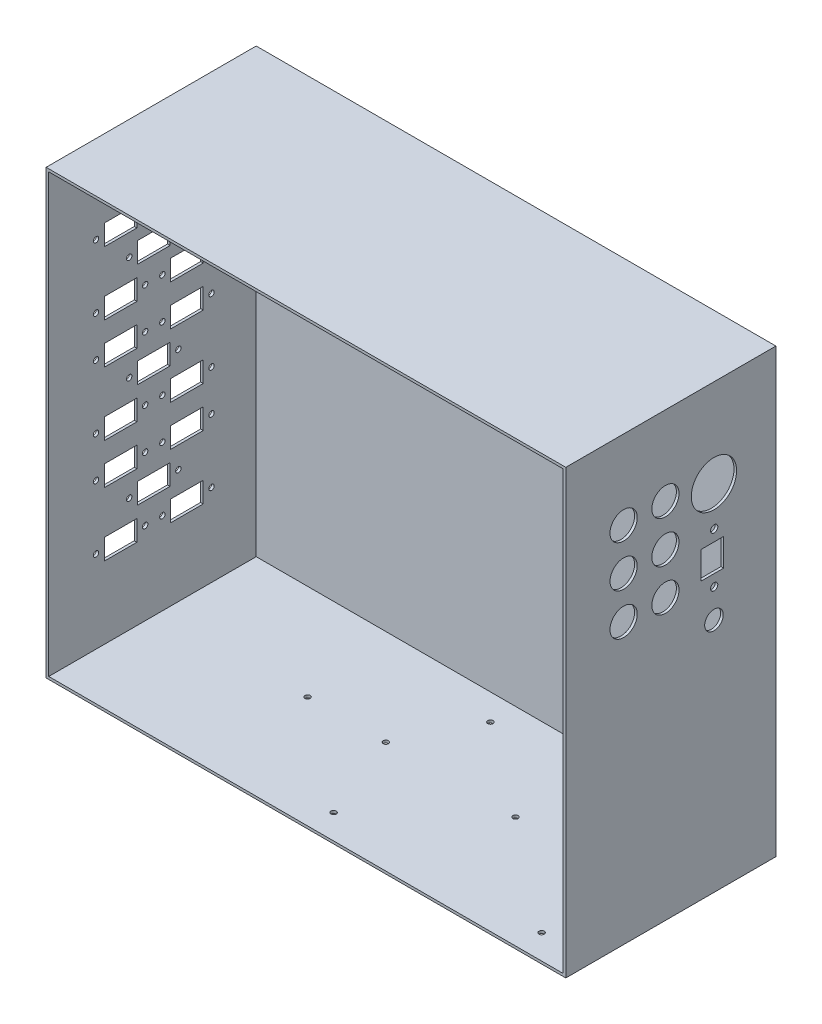
SolidWorks part; units mm, degrees
ref_plane "Front Plane" through (0, 0, 0) normal (0, 0, 1) x (1, 0, 0)
ref_plane "Top Plane" through (0, 0, 0) normal (0, 1, 0) x (1, 0, 0)
ref_plane "Right Plane" through (0, 0, 0) normal (1, 0, 0) x (0, 0, -1)
sketch "Sketch2" plane through (0, 0, 0) normal (0, 0, 1) x (1, 0, 0)
  line L1 (-149.225, 127) -> (149.225, 127)
  line L2 (-149.225, 127) -> (-149.225, -127)
  line L3 (-149.225, -127) -> (149.225, -127)
  line L4 (149.225, 127) -> (149.225, -127)
  line L5 (-149.225, 127) -> (149.225, -127) construction
  line L6 (-149.225, -127) -> (149.225, 127) construction
  point P0 (0, 0)
  dimension "D1" = 298.45
  dimension "D2" = 254
extrude "Boss-Extrude1" add sketch "Sketch2" along normal blind 120.65
shell "Shell1" thickness 1.5
sketch "Sketch3" plane through (149.225, 0, 0) normal (1, 0, 0) x (0, 0, -1)
  line L0 (-40.4352, 50.2841) -> (-40.4352, 57.3961) construction
  line L1 (-24.3484, 28.5671) -> (-24.2403, 50.2841) construction
  line L2 (-101.6, 95.7164) -> (-19.05, 95.7164) construction
  line L3 (-101.6, 95.7164) -> (-101.6, -88.9) construction
  line L4 (-101.6, -88.9) -> (-19.05, -88.9) construction
  line L5 (-19.05, 95.7164) -> (-19.05, -88.9) construction
  line L6 (-24.3484, 28.5671) -> (-30.4022, 28.5671) construction
  line L7 (-46.489, 28.5671) -> (-46.5749, 50.2841) construction
  line L8 (-24.2403, 50.2841) -> (-30.4022, 50.2841) construction
  line L9 (-30.4022, 50.2841) -> (-30.4022, 57.4161) construction
  line L10 (-40.4352, 28.5671) -> (-46.489, 28.5671) construction
  line L11 (-40.4352, 21.4551) -> (-40.4352, 28.5671) construction
  line L12 (-40.4352, 21.4551) -> (-30.4022, 21.4551) construction
  line L13 (-30.4022, 21.4551) -> (-30.4022, 28.5671) construction
  line L14 (-40.4352, 57.3961) -> (-30.4022, 57.4161) construction
  line L15 (-40.4352, 50.2841) -> (-46.5749, 50.2841) construction
  line L16 (-46.532, 39.4256) -> (-24.2943, 39.4256) construction
  line L17 (-35.4187, 23.6) -> (-35.4187, 57.4061) construction
  line L18 (-43.0873, 31.5516) -> (-43.0873, 47.2996)
  line L19 (-43.0873, 31.5516) -> (-30.0063, 31.5516)
  line L20 (-30.0063, 31.5516) -> (-30.0063, 47.2996)
  line L21 (-43.0873, 47.2996) -> (-30.0063, 47.2996)
  line L24 (-120.65, -127) -> (-120.65, 127) construction
  line L25 (-120.65, -127) -> (0, -127) construction
  circle A0 centre (-87.4395, 33.5559) radius 7.8105
  circle A1 centre (-63.4395, 33.5559) radius 7.8105
  circle A2 centre (-63.4395, 57.5559) radius 7.8105
  circle A3 centre (-63.4395, 81.5559) radius 7.8105
  circle A4 centre (-87.4395, 57.5559) radius 7.8105
  circle A5 centre (-87.4395, 81.5559) radius 7.8105
  circle A6 centre (-35.4187, 25.0111) radius 2.0638
  circle A7 centre (-35.4187, 53.8401) radius 2.0638
  circle A8 centre (-35.56, 8.5011) radius 5.334
  circle A9 centre (-35.56, 76.3489) radius 13.0175
  dimension "D1" = 15.621
  dimension "D4" = 82.55
  dimension "D5" = 14.1605
  dimension "D7" = 19.3675
  dimension "D10" = 28.829
  dimension "D11" = 6.5405
  dimension "D21" = 16.51
  dimension "D6" = 14.1605
  dimension "D8" = 0.512
  dimension "D9" = 13.081
  dimension "D12" = 21.717
  dimension "D13" = 15.748
  dimension "D14" = 7.6686
  dimension "D15" = 0.285
  dimension "D16" = 10.033
  dimension "D17" = 0.227
  dimension "D18" = 16.51
  dimension "D19" = 19.05
  dimension "D20" = 38.1
  dimension "D22" = 0.115
  dimension "D23" = 6.1397
  dimension "D24" = 16.51
  dimension "D2" = 2
  dimension "D3" = 3
extrude "PT Connector Cutouts" cut sketch "Sketch3" against normal up to next
sketch "Sketch4" plane through (-149.225, 0, 0) normal (-1, 0, 0) x (0, 0, 1)
  line L0 (41.275, 72.2563) -> (41.275, 84.0563) construction
  line L1 (31.925, 84.0563) -> (31.925, 72.2563)
  line L2 (31.925, 84.0563) -> (50.625, 84.0563)
  line L3 (50.625, 84.0563) -> (50.625, 72.2563)
  line L4 (31.925, 72.2563) -> (50.625, 72.2563)
  line L10 (22.225, -88.9) -> (98.425, -88.9) construction
  line L11 (22.225, -88.9) -> (22.225, 88.9) construction
  line L12 (22.225, 88.9) -> (98.425, 88.9) construction
  line L13 (98.425, -88.9) -> (98.425, 88.9) construction
  line L73 (120.65, 127) -> (0, 127) construction
  line L74 (0, 127) -> (0, -127) construction
  line L75 (31.925, 86.0563) -> (27.1625, 84.0563) construction
  line L81 (31.925, 70.2563) -> (50.625, 70.2563) construction
  line L83 (31.925, 86.0563) -> (50.625, 86.0563) construction
  line L84 (50.625, 86.0563) -> (55.3875, 84.0563) construction
  line L85 (31.925, 70.2563) -> (27.1625, 72.2563) construction
  line L86 (50.625, 70.2563) -> (55.3875, 72.2563) construction
  line L87 (31.925, 84.0563) -> (50.625, 84.0563) construction
  line L89 (31.925, 72.2563) -> (50.625, 72.2563) construction
  line L91 (31.925, 84.0563) -> (50.625, 84.0563) construction
  line L92 (24.275, 72.2563) -> (24.275, 84.0563) construction
  line L93 (24.275, 72.2563) -> (27.1625, 72.2563) construction
  line L94 (58.275, 72.2563) -> (58.275, 84.0563) construction
  line L95 (24.275, 84.0563) -> (27.1625, 84.0563) construction
  line L98 (55.3875, 84.0563) -> (58.275, 84.0563) construction
  line L99 (55.3875, 72.2563) -> (58.275, 72.2563) construction
  line L100 (31.925, 72.2563) -> (50.625, 72.2563) construction
  line L170 (120.65, -127) -> (0, -127) construction
  line L171 (70.025, 84.0563) -> (70.025, 72.2563)
  line L172 (70.025, 84.0563) -> (88.725, 84.0563)
  line L173 (88.725, 84.0563) -> (88.725, 72.2563)
  line L174 (70.025, 72.2563) -> (88.725, 72.2563)
  line L175 (79.375, 72.2563) -> (79.375, 84.0563) construction
  line L176 (70.025, 86.0563) -> (65.2625, 84.0563) construction
  line L177 (70.025, 70.2563) -> (88.725, 70.2563) construction
  line L178 (70.025, 86.0563) -> (88.725, 86.0563) construction
  line L179 (88.725, 86.0563) -> (93.4875, 84.0563) construction
  line L180 (70.025, 70.2563) -> (65.2625, 72.2563) construction
  line L181 (88.725, 70.2563) -> (93.4875, 72.2563) construction
  line L182 (70.025, 84.0563) -> (88.725, 84.0563) construction
  line L183 (70.025, 72.2563) -> (88.725, 72.2563) construction
  line L184 (70.025, 84.0563) -> (88.725, 84.0563) construction
  line L185 (62.375, 72.2563) -> (62.375, 84.0563) construction
  line L186 (62.375, 72.2563) -> (65.2625, 72.2563) construction
  line L187 (96.375, 72.2563) -> (96.375, 84.0563) construction
  line L188 (62.375, 84.0563) -> (65.2625, 84.0563) construction
  line L189 (93.4875, 84.0563) -> (96.375, 84.0563) construction
  line L190 (93.4875, 72.2563) -> (96.375, 72.2563) construction
  line L191 (70.025, 72.2563) -> (88.725, 72.2563) construction
  line L213 (70.025, 47.5438) -> (70.025, 35.7438)
  line L214 (70.025, 47.5438) -> (88.725, 47.5438)
  line L215 (88.725, 47.5438) -> (88.725, 35.7438)
  line L216 (70.025, 35.7438) -> (88.725, 35.7438)
  line L217 (79.375, 35.7438) -> (79.375, 47.5438) construction
  line L218 (70.025, 49.5438) -> (65.2625, 47.5438) construction
  line L219 (70.025, 33.7438) -> (88.725, 33.7438) construction
  line L220 (70.025, 49.5438) -> (88.725, 49.5438) construction
  line L221 (88.725, 49.5438) -> (93.4875, 47.5438) construction
  line L222 (70.025, 33.7438) -> (65.2625, 35.7438) construction
  line L223 (88.725, 33.7438) -> (93.4875, 35.7438) construction
  line L224 (70.025, 47.5438) -> (88.725, 47.5438) construction
  line L225 (70.025, 35.7438) -> (88.725, 35.7438) construction
  line L226 (70.025, 47.5438) -> (88.725, 47.5438) construction
  line L227 (62.375, 35.7438) -> (62.375, 47.5438) construction
  line L228 (62.375, 35.7438) -> (65.2625, 35.7438) construction
  line L229 (96.375, 35.7438) -> (96.375, 47.5438) construction
  line L230 (62.375, 47.5438) -> (65.2625, 47.5438) construction
  line L231 (93.4875, 47.5438) -> (96.375, 47.5438) construction
  line L232 (93.4875, 35.7438) -> (96.375, 35.7438) construction
  line L233 (70.025, 35.7438) -> (88.725, 35.7438) construction
  line L234 (70.025, 24.1563) -> (70.025, 12.3563)
  line L235 (70.025, 24.1563) -> (88.725, 24.1563)
  line L236 (88.725, 24.1563) -> (88.725, 12.3563)
  line L237 (70.025, 12.3563) -> (88.725, 12.3563)
  line L238 (79.375, 12.3563) -> (79.375, 24.1563) construction
  line L239 (70.025, 26.1563) -> (65.2625, 24.1563) construction
  line L240 (70.025, 10.3563) -> (88.725, 10.3563) construction
  line L241 (70.025, 26.1563) -> (88.725, 26.1563) construction
  line L242 (88.725, 26.1563) -> (93.4875, 24.1563) construction
  line L243 (70.025, 10.3563) -> (65.2625, 12.3563) construction
  line L244 (88.725, 10.3563) -> (93.4875, 12.3563) construction
  line L245 (70.025, 24.1563) -> (88.725, 24.1563) construction
  line L246 (70.025, 12.3563) -> (88.725, 12.3563) construction
  line L247 (70.025, 24.1563) -> (88.725, 24.1563) construction
  line L248 (62.375, 12.3563) -> (62.375, 24.1563) construction
  line L249 (62.375, 12.3563) -> (65.2625, 12.3563) construction
  line L250 (96.375, 12.3563) -> (96.375, 24.1563) construction
  line L251 (62.375, 24.1563) -> (65.2625, 24.1563) construction
  line L252 (93.4875, 24.1563) -> (96.375, 24.1563) construction
  line L253 (93.4875, 12.3563) -> (96.375, 12.3563) construction
  line L254 (70.025, 12.3563) -> (88.725, 12.3563) construction
  line L276 (70.025, -12.3562) -> (70.025, -24.1562)
  line L277 (70.025, -12.3562) -> (88.725, -12.3562)
  line L278 (88.725, -12.3562) -> (88.725, -24.1562)
  line L279 (70.025, -24.1562) -> (88.725, -24.1562)
  line L280 (79.375, -24.1562) -> (79.375, -12.3562) construction
  line L281 (70.025, -10.3562) -> (65.2625, -12.3562) construction
  line L282 (70.025, -26.1562) -> (88.725, -26.1562) construction
  line L283 (70.025, -10.3562) -> (88.725, -10.3562) construction
  line L284 (88.725, -10.3562) -> (93.4875, -12.3562) construction
  line L285 (70.025, -26.1562) -> (65.2625, -24.1562) construction
  line L286 (88.725, -26.1562) -> (93.4875, -24.1562) construction
  line L287 (70.025, -12.3562) -> (88.725, -12.3562) construction
  line L288 (70.025, -24.1562) -> (88.725, -24.1562) construction
  line L289 (70.025, -12.3562) -> (88.725, -12.3562) construction
  line L290 (62.375, -24.1562) -> (62.375, -12.3562) construction
  line L291 (62.375, -24.1562) -> (65.2625, -24.1562) construction
  line L292 (96.375, -24.1562) -> (96.375, -12.3562) construction
  line L293 (62.375, -12.3562) -> (65.2625, -12.3562) construction
  line L294 (93.4875, -12.3562) -> (96.375, -12.3562) construction
  line L295 (93.4875, -24.1562) -> (96.375, -24.1562) construction
  line L296 (70.025, -24.1562) -> (88.725, -24.1562) construction
  line L297 (70.025, -35.7437) -> (70.025, -47.5437)
  line L298 (70.025, -35.7437) -> (88.725, -35.7437)
  line L299 (88.725, -35.7437) -> (88.725, -47.5437)
  line L300 (70.025, -47.5437) -> (88.725, -47.5437)
  line L301 (79.375, -47.5437) -> (79.375, -35.7437) construction
  line L302 (70.025, -33.7437) -> (65.2625, -35.7437) construction
  line L303 (70.025, -49.5437) -> (88.725, -49.5437) construction
  line L304 (70.025, -33.7437) -> (88.725, -33.7437) construction
  line L305 (88.725, -33.7437) -> (93.4875, -35.7437) construction
  line L306 (70.025, -49.5437) -> (65.2625, -47.5437) construction
  line L307 (88.725, -49.5437) -> (93.4875, -47.5437) construction
  line L308 (70.025, -35.7437) -> (88.725, -35.7437) construction
  line L309 (70.025, -47.5437) -> (88.725, -47.5437) construction
  line L310 (70.025, -35.7437) -> (88.725, -35.7437) construction
  line L311 (62.375, -47.5437) -> (62.375, -35.7437) construction
  line L312 (62.375, -47.5437) -> (65.2625, -47.5437) construction
  line L313 (96.375, -47.5437) -> (96.375, -35.7437) construction
  line L314 (62.375, -35.7437) -> (65.2625, -35.7437) construction
  line L315 (93.4875, -35.7437) -> (96.375, -35.7437) construction
  line L316 (93.4875, -47.5437) -> (96.375, -47.5437) construction
  line L317 (70.025, -47.5437) -> (88.725, -47.5437) construction
  line L339 (70.025, -72.2562) -> (70.025, -84.0562)
  line L340 (70.025, -72.2562) -> (88.725, -72.2562)
  line L341 (88.725, -72.2562) -> (88.725, -84.0562)
  line L342 (70.025, -84.0562) -> (88.725, -84.0562)
  line L343 (79.375, -84.0562) -> (79.375, -72.2562) construction
  line L344 (70.025, -70.2562) -> (65.2625, -72.2562) construction
  line L345 (70.025, -86.0562) -> (88.725, -86.0562) construction
  line L346 (70.025, -70.2562) -> (88.725, -70.2562) construction
  line L347 (88.725, -70.2562) -> (93.4875, -72.2562) construction
  line L348 (70.025, -86.0562) -> (65.2625, -84.0562) construction
  line L349 (88.725, -86.0562) -> (93.4875, -84.0562) construction
  line L350 (70.025, -72.2562) -> (88.725, -72.2562) construction
  line L351 (70.025, -84.0562) -> (88.725, -84.0562) construction
  line L352 (70.025, -72.2562) -> (88.725, -72.2562) construction
  line L353 (62.375, -84.0562) -> (62.375, -72.2562) construction
  line L354 (62.375, -84.0562) -> (65.2625, -84.0562) construction
  line L355 (96.375, -84.0562) -> (96.375, -72.2562) construction
  line L356 (62.375, -72.2562) -> (65.2625, -72.2562) construction
  line L357 (93.4875, -72.2562) -> (96.375, -72.2562) construction
  line L358 (93.4875, -84.0562) -> (96.375, -84.0562) construction
  line L359 (70.025, -84.0562) -> (88.725, -84.0562) construction
  line L360 (50.975, 65.8) -> (50.975, 54)
  line L361 (50.975, 65.8) -> (69.675, 65.8)
  line L362 (69.675, 65.8) -> (69.675, 54)
  line L363 (50.975, 54) -> (69.675, 54)
  line L364 (60.325, 54) -> (60.325, 65.8) construction
  line L365 (50.975, 67.8) -> (46.2125, 65.8) construction
  line L366 (50.975, 52) -> (69.675, 52) construction
  line L367 (50.975, 67.8) -> (69.675, 67.8) construction
  line L368 (69.675, 67.8) -> (74.4375, 65.8) construction
  line L369 (50.975, 52) -> (46.2125, 54) construction
  line L370 (69.675, 52) -> (74.4375, 54) construction
  line L371 (50.975, 65.8) -> (69.675, 65.8) construction
  line L372 (50.975, 54) -> (69.675, 54) construction
  line L373 (50.975, 65.8) -> (69.675, 65.8) construction
  line L374 (43.325, 54) -> (43.325, 65.8) construction
  line L375 (43.325, 54) -> (46.2125, 54) construction
  line L376 (77.325, 54) -> (77.325, 65.8) construction
  line L377 (43.325, 65.8) -> (46.2125, 65.8) construction
  line L378 (74.4375, 65.8) -> (77.325, 65.8) construction
  line L379 (74.4375, 54) -> (77.325, 54) construction
  line L380 (50.975, 54) -> (69.675, 54) construction
  line L381 (31.925, 47.5438) -> (31.925, 35.7438)
  line L382 (31.925, 47.5438) -> (50.625, 47.5438)
  line L383 (50.625, 47.5438) -> (50.625, 35.7438)
  line L384 (31.925, 35.7438) -> (50.625, 35.7438)
  line L385 (41.275, 35.7438) -> (41.275, 47.5438) construction
  line L386 (31.925, 49.5438) -> (27.1625, 47.5438) construction
  line L387 (31.925, 33.7438) -> (50.625, 33.7438) construction
  line L388 (31.925, 49.5438) -> (50.625, 49.5438) construction
  line L389 (50.625, 49.5438) -> (55.3875, 47.5438) construction
  line L390 (31.925, 33.7438) -> (27.1625, 35.7438) construction
  line L391 (50.625, 33.7438) -> (55.3875, 35.7438) construction
  line L392 (31.925, 47.5438) -> (50.625, 47.5438) construction
  line L393 (31.925, 35.7438) -> (50.625, 35.7438) construction
  line L394 (31.925, 47.5438) -> (50.625, 47.5438) construction
  line L395 (24.275, 35.7438) -> (24.275, 47.5438) construction
  line L396 (24.275, 35.7438) -> (27.1625, 35.7438) construction
  line L397 (58.275, 35.7438) -> (58.275, 47.5438) construction
  line L398 (24.275, 47.5438) -> (27.1625, 47.5438) construction
  line L399 (55.3875, 47.5438) -> (58.275, 47.5438) construction
  line L400 (55.3875, 35.7438) -> (58.275, 35.7438) construction
  line L401 (31.925, 35.7438) -> (50.625, 35.7438) construction
  line L402 (31.925, 24.1563) -> (31.925, 12.3563)
  line L403 (31.925, 24.1563) -> (50.625, 24.1563)
  line L404 (50.625, 24.1563) -> (50.625, 12.3563)
  line L405 (31.925, 12.3563) -> (50.625, 12.3563)
  line L406 (41.275, 12.3563) -> (41.275, 24.1563) construction
  line L407 (31.925, 26.1563) -> (27.1625, 24.1563) construction
  line L408 (31.925, 10.3563) -> (50.625, 10.3563) construction
  line L409 (31.925, 26.1563) -> (50.625, 26.1563) construction
  line L410 (50.625, 26.1563) -> (55.3875, 24.1563) construction
  line L411 (31.925, 10.3563) -> (27.1625, 12.3563) construction
  line L412 (50.625, 10.3563) -> (55.3875, 12.3563) construction
  line L413 (31.925, 24.1563) -> (50.625, 24.1563) construction
  line L414 (31.925, 12.3563) -> (50.625, 12.3563) construction
  line L415 (31.925, 24.1563) -> (50.625, 24.1563) construction
  line L416 (24.275, 12.3563) -> (24.275, 24.1563) construction
  line L417 (24.275, 12.3563) -> (27.1625, 12.3563) construction
  line L418 (58.275, 12.3563) -> (58.275, 24.1563) construction
  line L419 (24.275, 24.1563) -> (27.1625, 24.1563) construction
  line L420 (55.3875, 24.1563) -> (58.275, 24.1563) construction
  line L421 (55.3875, 12.3563) -> (58.275, 12.3563) construction
  line L422 (31.925, 12.3563) -> (50.625, 12.3563) construction
  line L423 (50.975, 5.9) -> (50.975, -5.9)
  line L424 (50.975, 5.9) -> (69.675, 5.9)
  line L425 (69.675, 5.9) -> (69.675, -5.9)
  line L426 (50.975, -5.9) -> (69.675, -5.9)
  line L427 (60.325, -5.9) -> (60.325, 5.9) construction
  line L428 (50.975, 7.9) -> (46.2125, 5.9) construction
  line L429 (50.975, -7.9) -> (69.675, -7.9) construction
  line L430 (50.975, 7.9) -> (69.675, 7.9) construction
  line L431 (69.675, 7.9) -> (74.4375, 5.9) construction
  line L432 (50.975, -7.9) -> (46.2125, -5.9) construction
  line L433 (69.675, -7.9) -> (74.4375, -5.9) construction
  line L434 (50.975, 5.9) -> (69.675, 5.9) construction
  line L435 (50.975, -5.9) -> (69.675, -5.9) construction
  line L436 (50.975, 5.9) -> (69.675, 5.9) construction
  line L437 (43.325, -5.9) -> (43.325, 5.9) construction
  line L438 (43.325, -5.9) -> (46.2125, -5.9) construction
  line L439 (77.325, -5.9) -> (77.325, 5.9) construction
  line L440 (43.325, 5.9) -> (46.2125, 5.9) construction
  line L441 (74.4375, 5.9) -> (77.325, 5.9) construction
  line L442 (74.4375, -5.9) -> (77.325, -5.9) construction
  line L443 (50.975, -5.9) -> (69.675, -5.9) construction
  line L444 (31.925, -12.3562) -> (31.925, -24.1562)
  line L445 (31.925, -12.3562) -> (50.625, -12.3562)
  line L446 (50.625, -12.3562) -> (50.625, -24.1562)
  line L447 (31.925, -24.1562) -> (50.625, -24.1562)
  line L448 (41.275, -24.1562) -> (41.275, -12.3562) construction
  line L449 (31.925, -10.3562) -> (27.1625, -12.3562) construction
  line L450 (31.925, -26.1562) -> (50.625, -26.1562) construction
  line L451 (31.925, -10.3562) -> (50.625, -10.3562) construction
  line L452 (50.625, -10.3562) -> (55.3875, -12.3562) construction
  line L453 (31.925, -26.1562) -> (27.1625, -24.1562) construction
  line L454 (50.625, -26.1562) -> (55.3875, -24.1562) construction
  line L455 (31.925, -12.3562) -> (50.625, -12.3562) construction
  line L456 (31.925, -24.1562) -> (50.625, -24.1562) construction
  line L457 (31.925, -12.3562) -> (50.625, -12.3562) construction
  line L458 (24.275, -24.1562) -> (24.275, -12.3562) construction
  line L459 (24.275, -24.1562) -> (27.1625, -24.1562) construction
  line L460 (58.275, -24.1562) -> (58.275, -12.3562) construction
  line L461 (24.275, -12.3562) -> (27.1625, -12.3562) construction
  line L462 (55.3875, -12.3562) -> (58.275, -12.3562) construction
  line L463 (55.3875, -24.1562) -> (58.275, -24.1562) construction
  line L464 (31.925, -24.1562) -> (50.625, -24.1562) construction
  line L465 (31.925, -35.7437) -> (31.925, -47.5437)
  line L466 (31.925, -35.7437) -> (50.625, -35.7437)
  line L467 (50.625, -35.7437) -> (50.625, -47.5437)
  line L468 (31.925, -47.5437) -> (50.625, -47.5437)
  line L469 (41.275, -47.5437) -> (41.275, -35.7437) construction
  line L470 (31.925, -33.7437) -> (27.1625, -35.7437) construction
  line L471 (31.925, -49.5437) -> (50.625, -49.5437) construction
  line L472 (31.925, -33.7437) -> (50.625, -33.7437) construction
  line L473 (50.625, -33.7437) -> (55.3875, -35.7437) construction
  line L474 (31.925, -49.5437) -> (27.1625, -47.5437) construction
  line L475 (50.625, -49.5437) -> (55.3875, -47.5437) construction
  line L476 (31.925, -35.7437) -> (50.625, -35.7437) construction
  line L477 (31.925, -47.5437) -> (50.625, -47.5437) construction
  line L478 (31.925, -35.7437) -> (50.625, -35.7437) construction
  line L479 (24.275, -47.5437) -> (24.275, -35.7437) construction
  line L480 (24.275, -47.5437) -> (27.1625, -47.5437) construction
  line L481 (58.275, -47.5437) -> (58.275, -35.7437) construction
  line L482 (24.275, -35.7437) -> (27.1625, -35.7437) construction
  line L483 (55.3875, -35.7437) -> (58.275, -35.7437) construction
  line L484 (55.3875, -47.5437) -> (58.275, -47.5437) construction
  line L485 (31.925, -47.5437) -> (50.625, -47.5437) construction
  line L486 (50.975, -54) -> (50.975, -65.8)
  line L487 (50.975, -54) -> (69.675, -54)
  line L488 (69.675, -54) -> (69.675, -65.8)
  line L489 (50.975, -65.8) -> (69.675, -65.8)
  line L490 (60.325, -65.8) -> (60.325, -54) construction
  line L491 (50.975, -52) -> (46.2125, -54) construction
  line L492 (50.975, -67.8) -> (69.675, -67.8) construction
  line L493 (50.975, -52) -> (69.675, -52) construction
  line L494 (69.675, -52) -> (74.4375, -54) construction
  line L495 (50.975, -67.8) -> (46.2125, -65.8) construction
  line L496 (69.675, -67.8) -> (74.4375, -65.8) construction
  line L497 (50.975, -54) -> (69.675, -54) construction
  line L498 (50.975, -65.8) -> (69.675, -65.8) construction
  line L499 (50.975, -54) -> (69.675, -54) construction
  line L500 (43.325, -65.8) -> (43.325, -54) construction
  line L501 (43.325, -65.8) -> (46.2125, -65.8) construction
  line L502 (77.325, -65.8) -> (77.325, -54) construction
  line L503 (43.325, -54) -> (46.2125, -54) construction
  line L504 (74.4375, -54) -> (77.325, -54) construction
  line L505 (74.4375, -65.8) -> (77.325, -65.8) construction
  line L506 (50.975, -65.8) -> (69.675, -65.8) construction
  line L507 (31.925, -72.2562) -> (31.925, -84.0562)
  line L508 (31.925, -72.2562) -> (50.625, -72.2562)
  line L509 (50.625, -72.2562) -> (50.625, -84.0562)
  line L510 (31.925, -84.0562) -> (50.625, -84.0562)
  line L511 (41.275, -84.0562) -> (41.275, -72.2562) construction
  line L512 (31.925, -70.2562) -> (27.1625, -72.2562) construction
  line L513 (31.925, -86.0562) -> (50.625, -86.0562) construction
  line L514 (31.925, -70.2562) -> (50.625, -70.2562) construction
  line L515 (50.625, -70.2562) -> (55.3875, -72.2562) construction
  line L516 (31.925, -86.0562) -> (27.1625, -84.0562) construction
  line L517 (50.625, -86.0562) -> (55.3875, -84.0562) construction
  line L518 (31.925, -72.2562) -> (50.625, -72.2562) construction
  line L519 (31.925, -84.0562) -> (50.625, -84.0562) construction
  line L520 (31.925, -72.2562) -> (50.625, -72.2562) construction
  line L521 (24.275, -84.0562) -> (24.275, -72.2562) construction
  line L522 (24.275, -84.0562) -> (27.1625, -84.0562) construction
  line L523 (58.275, -84.0562) -> (58.275, -72.2562) construction
  line L524 (24.275, -72.2562) -> (27.1625, -72.2562) construction
  line L525 (55.3875, -72.2562) -> (58.275, -72.2562) construction
  line L526 (55.3875, -84.0562) -> (58.275, -84.0562) construction
  line L527 (31.925, -84.0562) -> (50.625, -84.0562) construction
  circle A0 centre (55.3875, 78.1563) radius 1.55
  circle A1 centre (27.1625, 78.1563) radius 1.55
  circle A2 centre (93.4875, 78.1563) radius 1.55
  circle A3 centre (65.2625, 78.1563) radius 1.55
  circle A6 centre (93.4875, 41.6438) radius 1.55
  circle A7 centre (65.2625, 41.6438) radius 1.55
  circle A8 centre (93.4875, 18.2563) radius 1.55
  circle A9 centre (65.2625, 18.2563) radius 1.55
  circle A12 centre (93.4875, -18.2562) radius 1.55
  circle A13 centre (65.2625, -18.2562) radius 1.55
  circle A14 centre (93.4875, -41.6437) radius 1.55
  circle A15 centre (65.2625, -41.6437) radius 1.55
  circle A18 centre (93.4875, -78.1562) radius 1.55
  circle A19 centre (65.2625, -78.1562) radius 1.55
  circle A20 centre (74.4375, 59.9) radius 1.55
  circle A21 centre (46.2125, 59.9) radius 1.55
  circle A22 centre (55.3875, 41.6438) radius 1.55
  circle A23 centre (27.1625, 41.6438) radius 1.55
  circle A24 centre (55.3875, 18.2563) radius 1.55
  circle A25 centre (27.1625, 18.2563) radius 1.55
  circle A26 centre (74.4375, 0) radius 1.55
  circle A27 centre (46.2125, 0) radius 1.55
  circle A28 centre (55.3875, -18.2562) radius 1.55
  circle A29 centre (27.1625, -18.2562) radius 1.55
  circle A30 centre (55.3875, -41.6437) radius 1.55
  circle A31 centre (27.1625, -41.6437) radius 1.55
  circle A32 centre (74.4375, -59.9) radius 1.55
  circle A33 centre (46.2125, -59.9) radius 1.55
  circle A34 centre (55.3875, -78.1562) radius 1.55
  circle A35 centre (27.1625, -78.1562) radius 1.55
  point P0 (41.275, 78.1563)
  point P10 (41.275, 78.1563)
  point P14 (79.375, 78.1563)
  point P30 (79.375, 78.1563)
  point P32 (79.375, 78.1563)
  point P33 (79.375, 78.1563)
  point P37 (79.375, 78.1563)
  point P76 (79.375, 41.6438)
  point P86 (79.375, 41.6438)
  point P88 (79.375, 41.6438)
  point P89 (79.375, 41.6438)
  point P93 (79.375, 41.6438)
  point P103 (79.375, 18.2563)
  point P113 (79.375, 18.2563)
  point P115 (79.375, 18.2563)
  point P116 (79.375, 18.2563)
  point P120 (79.375, 18.2563)
  point P141 (41.275, 78.1563)
  point P142 (41.275, 78.1563)
  point P146 (41.275, 78.1563)
  point P174 (79.375, -18.2562)
  point P184 (79.375, -18.2562)
  point P186 (79.375, -18.2562)
  point P187 (79.375, -18.2562)
  point P191 (79.375, -18.2562)
  point P201 (79.375, -41.6437)
  point P211 (79.375, -41.6437)
  point P213 (79.375, -41.6437)
  point P214 (79.375, -41.6437)
  point P218 (79.375, -41.6437)
  point P255 (79.375, -78.1562)
  point P265 (79.375, -78.1562)
  point P267 (79.375, -78.1562)
  point P268 (79.375, -78.1562)
  point P272 (79.375, -78.1562)
  point P282 (60.325, 59.9)
  point P292 (60.325, 59.9)
  point P294 (60.325, 59.9)
  point P295 (60.325, 59.9)
  point P299 (60.325, 59.9)
  point P309 (41.275, 41.6438)
  point P319 (41.275, 41.6438)
  point P321 (41.275, 41.6438)
  point P322 (41.275, 41.6438)
  point P326 (41.275, 41.6438)
  point P336 (41.275, 18.2563)
  point P346 (41.275, 18.2563)
  point P348 (41.275, 18.2563)
  point P349 (41.275, 18.2563)
  point P353 (41.275, 18.2563)
  point P363 (60.325, 0)
  point P373 (60.325, 0)
  point P375 (60.325, 0)
  point P376 (60.325, 0)
  point P380 (60.325, 0)
  point P390 (41.275, -18.2562)
  point P400 (41.275, -18.2562)
  point P402 (41.275, -18.2562)
  point P403 (41.275, -18.2562)
  point P407 (41.275, -18.2562)
  point P417 (41.275, -41.6437)
  point P427 (41.275, -41.6437)
  point P429 (41.275, -41.6437)
  point P430 (41.275, -41.6437)
  point P434 (41.275, -41.6437)
  point P444 (60.325, -59.9)
  point P454 (60.325, -59.9)
  point P456 (60.325, -59.9)
  point P457 (60.325, -59.9)
  point P461 (60.325, -59.9)
  point P471 (41.275, -78.1562)
  point P481 (41.275, -78.1562)
  point P483 (41.275, -78.1562)
  point P484 (41.275, -78.1562)
  point P488 (41.275, -78.1562)
  dimension "D1" = 18.7
  dimension "D4" = 4.7625
  dimension "D5" = 177.8
  dimension "D6" = 76.2
  dimension "D9" = 38.1
  dimension "D10" = 22.225
  dimension "D11" = 34
  dimension "D12" = 15.8
  dimension "D13" = 18.7
  dimension "D14" = 4.7625
extrude "Solenoid Connector Cutouts" cut sketch "Sketch4" against normal up to next (1.5 mm away)
sketch "Punchout Panel" plane through (-149.225, 0, 0) normal (-1, 0, 0) x (0, 0, 1)
  line L1 (98.425, 88.9) -> (22.225, 88.9) construction
  line L2 (98.425, 88.9) -> (98.425, -88.9) construction
  line L3 (98.425, -88.9) -> (22.225, -88.9) construction
  line L4 (22.225, 88.9) -> (22.225, -88.9) construction
  point P0 (60.325, 0)
sketch "Sketch5" plane through (0, -127, 127) normal (0, 1, 0) x (-1, 0, 0)
  line L1 (-126.2359, -15.4623) -> (-51.2359, -15.4623) construction
  line L2 (-126.2359, -15.4623) -> (-126.2359, -115.4623) construction
  line L3 (-126.2359, -115.4623) -> (-51.2359, -115.4623) construction
  line L4 (-51.2359, -15.4623) -> (-51.2359, -115.4623) construction
  line L5 (-6.7859, -15.4623) -> (68.2141, -15.4623) construction
  line L6 (-6.7859, -15.4623) -> (-6.7859, -115.4623) construction
  line L7 (-6.7859, -115.4623) -> (68.2141, -115.4623) construction
  line L8 (68.2141, -15.4623) -> (68.2141, -115.4623) construction
  circle A0 centre (-121.2359, -20.4623) radius 1.524
  circle A4 centre (-56.2359, -70.4623) radius 1.524
  circle A5 centre (-121.2359, -110.4623) radius 1.524
  circle A7 centre (-101.2359, -70.4623) radius 1.524
  circle A8 centre (-1.7859, -20.4623) radius 1.524
  circle A9 centre (63.2141, -70.4623) radius 1.524
  circle A10 centre (-1.7859, -110.4623) radius 1.524
  circle A11 centre (18.2141, -70.4623) radius 1.524
  dimension "D3" = 3.048
  dimension "D6" = 3.048
  dimension "D8" = 3.048
  dimension "D9" = 3.048
  dimension "D16" = 3.048
  dimension "D19" = 3.048
  dimension "D21" = 3.048
  dimension "D22" = 3.048
  dimension "D1" = 75
  dimension "D2" = 100
  dimension "D4" = 5
  dimension "D5" = 5
  dimension "D7" = 5
  dimension "D10" = 55
  dimension "D11" = 45
  dimension "D12" = 5
  dimension "D13" = 5
  dimension "D14" = 75
  dimension "D15" = 100
  dimension "D17" = 5
  dimension "D18" = 5
  dimension "D20" = 5
  dimension "D23" = 55
  dimension "D24" = 45
  dimension "D25" = 5
  dimension "D26" = 5
  dimension "D27" = 44.45
extrude "PCB Mounting Holes" cut sketch "Sketch5" along normal up to surface (1.5 mm away) up to face at (0, -125.5, 61.075)
